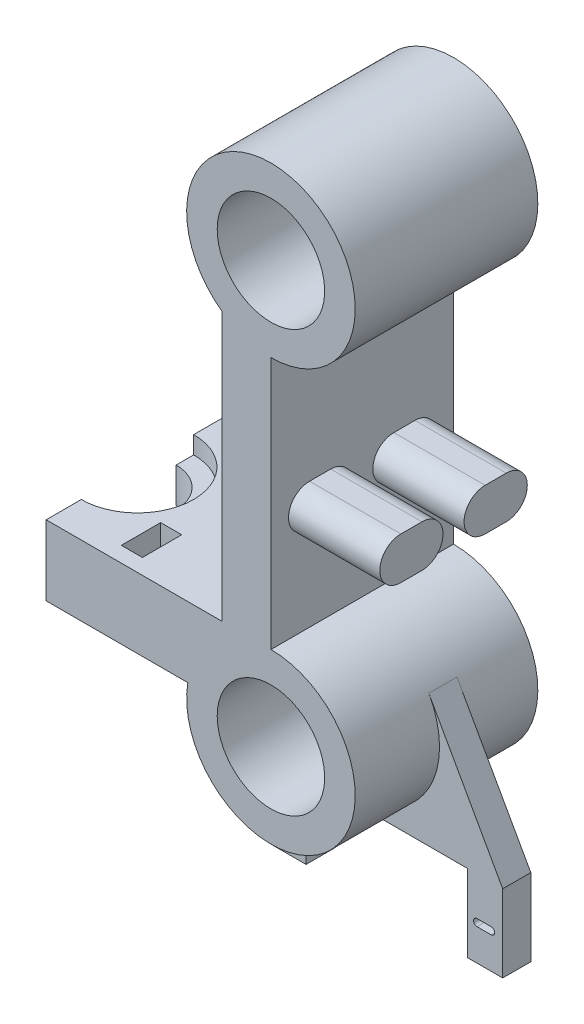
SolidWorks part; units mm, degrees
material "ABS"
ref_plane "Plano frontal" through (0, 0, 0) normal (0, 0, 1) x (1, 0, 0)
ref_plane "Plano superior" through (0, 0, 0) normal (0, 1, 0) x (1, 0, 0)
ref_plane "Plano direito" through (0, 0, 0) normal (1, 0, 0) x (0, 0, -1)
sketch "Esboço1" plane through (0, 0, 0) normal (0, 0, 1) x (1, 0, 0)
  line L0 (0, 30) -> (0, -30) construction
  line L1 (-7, 20.2532) -> (-7, -17.9992)
  line L2 (0, 18) -> (0, -18)
  line L3 (-7, 30) -> (-7, -30) construction
  line L4 (0, 30) -> (0, -30) construction
  line L5 (-11.832, -27.9992) -> (-32, -27.9992)
  line L6 (-32, -27.9992) -> (-32, -17.9992)
  line L7 (-32, -17.9992) -> (-7, -17.9992)
  circle A0 centre (0, 30) radius 7.65
  circle A1 centre (0, -30) radius 7.65
  arc A2 (0, 18) -> (-7, 20.2532) centre (0, 30) ccw
  arc A3 (-11.832, -27.9992) -> (0, -18) centre (0, -30) ccw
  point P4 (0, 0)
  point P13 (-7, -8)
  point P19 (-7, -18)
  point P20 (-11.832, -28)
  point P21 (-10.7192, -27.9992)
  dimension "D3" = 60
  dimension "D4" = 15.3
  dimension "D5" = 24
  dimension "D6" = 25
  dimension "D7" = 10
  dimension "D1" = 7
  dimension "D2" = 0
extrude "Ressalto-extrusão1" add sketch "Esboço1" along normal blind 26
sketch "Esboço3" plane through (-32, 0, 0) normal (-1, 0, 0) x (0, 0, 1)
  line L0 (13, -17.9992) -> (13, -27.9992) construction
  line L3 (13, -17.9992) -> (21, -17.9992)
  line L4 (21, -17.9992) -> (21, -20.4992)
  line L5 (21, -20.4992) -> (18.5, -20.4992)
  line L6 (18.5, -20.4992) -> (18.5, -25.4992)
  line L7 (18.5, -25.4992) -> (21, -25.4992)
  line L8 (21, -25.4992) -> (21, -27.9992)
  line L10 (21, -27.9992) -> (13, -27.9992)
  line L11 (13, -17.9992) -> (13, -27.9992)
  line L12 (26, -27.9992) -> (0, -27.9992) construction
  point P2 (13.0011, -18)
  point P3 (12.6592, -8)
  point P4 (13.1084, -18)
  point P5 (13, -27.9992)
  point P6 (18.5, -22.9992)
  point P15 (13, -8)
  point P16 (0, 0)
  point P17 (0, 0)
  point P18 (13, -18)
  point P19 (13, -8)
  dimension "D1" = 5
  dimension "D2" = 5.5
  dimension "D3" = 8
  dimension "D4" = 2.5
revolve "Corte-Revolução1" cut sketch "Esboço3" angle 360 about L0
sketch "Esboço4" plane through (-32, 0, 0) normal (-1, 0, 0) x (0, 0, 1)
  line L0 (13, -17.9992) -> (13, -18.4674) construction
  line L1 (26, -17.9992) -> (0, -17.9992) construction
  line L3 (7.5, -20.4992) -> (7.5, -25.4992) construction
  circle A0 centre (5, -22.9992) radius 1.75
  circle A1 centre (21, -22.9992) radius 1.75
  point P11 (7.5, -22.9992)
  dimension "D2" = 3.5
  dimension "D1" = 16
extrude "Corte-extrusão1" cut sketch "Esboço4" against normal blind 20
sketch "Esboço5" plane through (0, -17.9992, 0) normal (0, 1, 0) x (1, 0, 0)
  line L0 (-32, -5) -> (-22, -5) construction
  line L1 (-32, -5) -> (-32, 0) construction
  line L2 (-23.5, -2.2) -> (-20.5, -2.2)
  line L3 (-23.5, -2.2) -> (-23.5, -7.8)
  line L4 (-23.5, -7.8) -> (-20.5, -7.8)
  line L5 (-20.5, -2.2) -> (-20.5, -7.8)
  line L6 (-23.5, -2.2) -> (-20.5, -7.8) construction
  line L7 (-23.5, -7.8) -> (-20.5, -2.2) construction
  line L8 (-32, -13) -> (-16.3815, -13) construction
  line L9 (-23.5, -18.2) -> (-20.5, -23.8) construction
  line L10 (-23.5, -23.8) -> (-20.5, -18.2) construction
  line L11 (-32, -21) -> (-22, -21) construction
  line L12 (-20.5, -23.8) -> (-20.5, -18.2)
  line L13 (-23.5, -18.2) -> (-20.5, -18.2)
  line L14 (-23.5, -23.8) -> (-23.5, -18.2)
  line L15 (-23.5, -23.8) -> (-20.5, -23.8)
  dimension "D1" = 10
  dimension "D2" = 5.6
  dimension "D3" = 3
  dimension "D4" = 16
extrude "Corte-extrusão2" cut sketch "Esboço5" against normal blind 25
sketch "Esboço6" plane through (0, 0, 0) normal (1, 0, 0) x (0, 0, -1)
  line L0 (-13, 18) -> (-13, -18) construction
  line L1 (-26, 18) -> (0, 18) construction
  line L2 (-26, -18) -> (0, -18) construction
  line L3 (-20.9737, 0) -> (-5.0263, 0) construction
  line L4 (-49.8119, -6) -> (-16.3807, -6) construction
  line L5 (-17.5, -3) -> (-20.5, -3) construction
  line L6 (-17.5, -6) -> (-20.5, -6)
  line L7 (-17.5, 0) -> (-20.5, 0)
  line L8 (-8.5, -3) -> (-5.5, -3) construction
  line L9 (-8.5, -6) -> (-5.5, -6)
  line L10 (-8.5, 0) -> (-5.5, 0)
  circle A0 centre (-49.8119, 0) radius 6 construction
  arc A1 (-17.5, -6) -> (-17.5, 0) centre (-17.5, -3) ccw
  arc A2 (-20.5, 0) -> (-20.5, -6) centre (-20.5, -3) ccw
  arc A3 (-8.5, -6) -> (-8.5, 0) centre (-8.5, -3) cw
  arc A4 (-5.5, 0) -> (-5.5, -6) centre (-5.5, -3) cw
  point P10 (-13, 0)
  point P16 (-19, -3)
  point P21 (-17.2123, 0.7253)
  point P24 (-7, -3)
  dimension "D1" = 12
  dimension "D2" = 3
  dimension "D3" = 3
  dimension "D4" = 3
extrude "Ressalto-extrusão2" add sketch "Esboço6" along normal blind 13
sketch "Esboço7" plane through (0, 0, 26) normal (0, 0, 1) x (1, 0, 0)
  line L0 (-12, -30) -> (-12, -54)
  line L1 (-12, -54) -> (-7, -54)
  line L2 (-7, -54) -> (-7, -43)
  line L3 (-7, -43) -> (16, -43)
  line L4 (16, -43) -> (16, -54)
  line L5 (16, -54) -> (21, -54)
  line L6 (21, -54) -> (21, -43)
  line L7 (21, -43) -> (10.478, -24.1509)
  line L8 (-9.35, -49) -> (18.35, -49) construction
  line L9 (4.5, -49) -> (4.5, -43) construction
  line L10 (-10.35, -49) -> (-8.35, -49) construction
  line L11 (-10.35, -48.5) -> (-8.35, -48.5)
  line L12 (-10.35, -49.5) -> (-8.35, -49.5)
  line L13 (19.35, -49) -> (17.35, -49) construction
  line L14 (19.35, -49.5) -> (17.35, -49.5)
  line L15 (19.35, -48.5) -> (17.35, -48.5)
  arc A0 (-11.832, -27.9992) -> (0, -18) centre (0, -30) ccw construction
  arc A1 (-10.35, -48.5) -> (-10.35, -49.5) centre (-10.35, -49) ccw
  arc A2 (-8.35, -49.5) -> (-8.35, -48.5) centre (-8.35, -49) ccw
  arc A3 (19.35, -49.5) -> (19.35, -48.5) centre (19.35, -49) ccw
  arc A4 (17.35, -48.5) -> (17.35, -49.5) centre (17.35, -49) ccw
  arc A6 (-12, -30) -> (10.478, -24.1509) centre (0, -30) ccw
  point P15 (4.5, -49)
  point P16 (4.5, -43)
  point P20 (-9.35, -49)
  point P27 (18.35, -49)
  arc M20 (-11.832, -27.9992) -> (0, -18) centre (0, -30) ccw
  dimension "D6" = 0.5
  dimension "D1" = 23
  dimension "D2" = 11
  dimension "D3" = 1
  dimension "D4" = 5
  dimension "D5" = 6
  dimension "D7" = 2
  dimension "D8" = 27.7
extrude "Ressalto-extrusão3" add sketch "Esboço7" against normal blind 4 from offset 12 separate body contours L6 L7 L0 L1 L2 L3 L4 L5 A4 L15 A3 L14 A2 L12 A1 L11 M20
